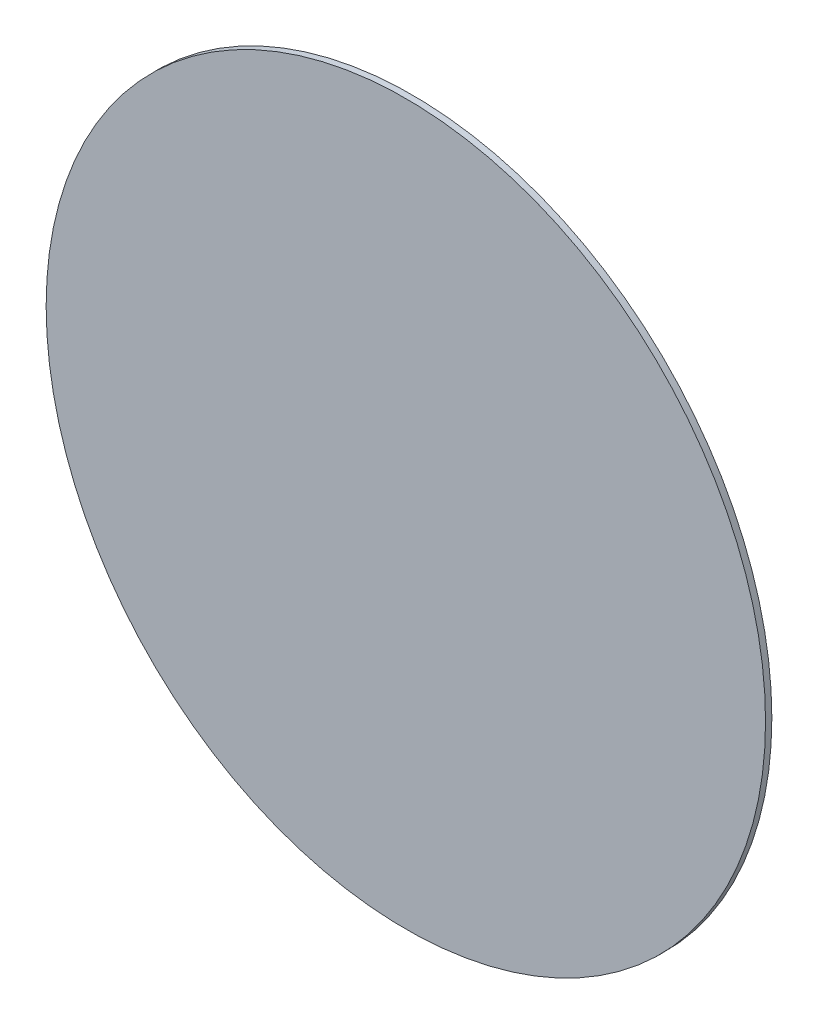
SolidWorks part; units mm, degrees
ref_plane "前视基准面" through (0, 0, 0) normal (0, 0, 1) x (1, 0, 0)
ref_plane "上视基准面" through (0, 0, 0) normal (0, 1, 0) x (1, 0, 0)
ref_plane "右视基准面" through (0, 0, 0) normal (1, 0, 0) x (0, 0, -1)
other "Configuration Table"
sketch "草图1" plane through (0, 0, 0) normal (0, 0, 1) x (1, 0, 0)
  circle A0 centre (0, 0) radius 114
  dimension "D1" = 228
extrude "凸台-拉伸1" add sketch "草图1" along normal blind 2
